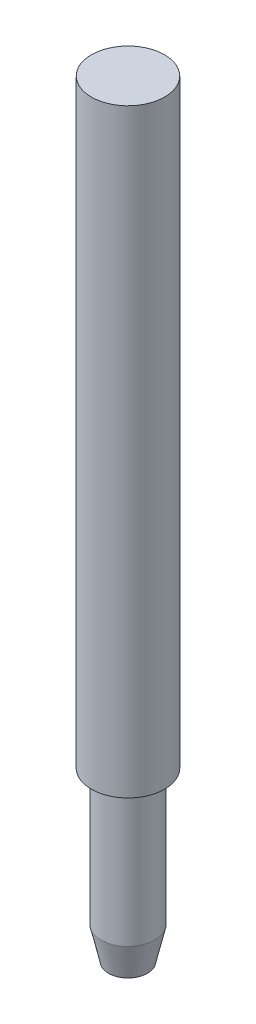
SolidWorks part; units mm, degrees
material "6061 Alloy"
ref_plane "Front Plane" through (0, 0, 0) normal (0, 0, 1) x (1, 0, 0)
ref_plane "Top Plane" through (0, 0, 0) normal (0, 1, 0) x (1, 0, 0)
ref_plane "Right Plane" through (0, 0, 0) normal (1, 0, 0) x (0, 0, -1)
sketch "Sketch1" plane through (0, 0, 0) normal (0, 1, 0) x (1, 0, 0)
  circle A0 centre (0, 0) radius 2.3813
  dimension "D1" = 4.7625
extrude "Boss-Extrude1" add sketch "Sketch1" along normal blind 38.9763
sketch "Sketch2" plane through (0, 0, 0) normal (0, -1, 0) x (1, 0, 0)
  circle A0 centre (0, 0) radius 1.7526
  dimension "D1" = 3.5052
extrude "Boss-Extrude2" add sketch "Sketch2" along normal blind 10.922
sketch "Sketch3" plane through (0, 0, 0) normal (1, 0, 0) x (0, 0, -1)
  line L0 (-1.7526, -10.922) -> (1.7526, -10.922) construction
  line L1 (-1.7526, -10.922) -> (1.7526, -10.922)
  line L2 (1.27, -10.922) -> (1.7526, -8.8053)
  line L3 (1.7526, -10.922) -> (1.7526, 0) construction
  line L4 (-1.27, -10.922) -> (-1.7526, -8.8053)
  line L5 (-1.7526, 0) -> (-1.7526, -10.922) construction
  line L6 (1.7526, -8.8053) -> (1.7526, -10.922)
  line L7 (0, -10.922) -> (0, -5.3561) construction
  dimension "D1" = 2.1167
  dimension "D2" = 2.54
  dimension "D3" = 3.5052
  dimension "D4" = 0.4826
revolve "Cut-Revolve1" cut sketch "Sketch3" angle 360 about L7
equation "\"D1@Sketch3\"=2/24"
equation "\"D4@Sketch3\"=(\"D3@Sketch3\"-\"D2@Sketch3\")/2"
equation "\"D1@Boss-Extrude2\"=0.450000in-0.02"
